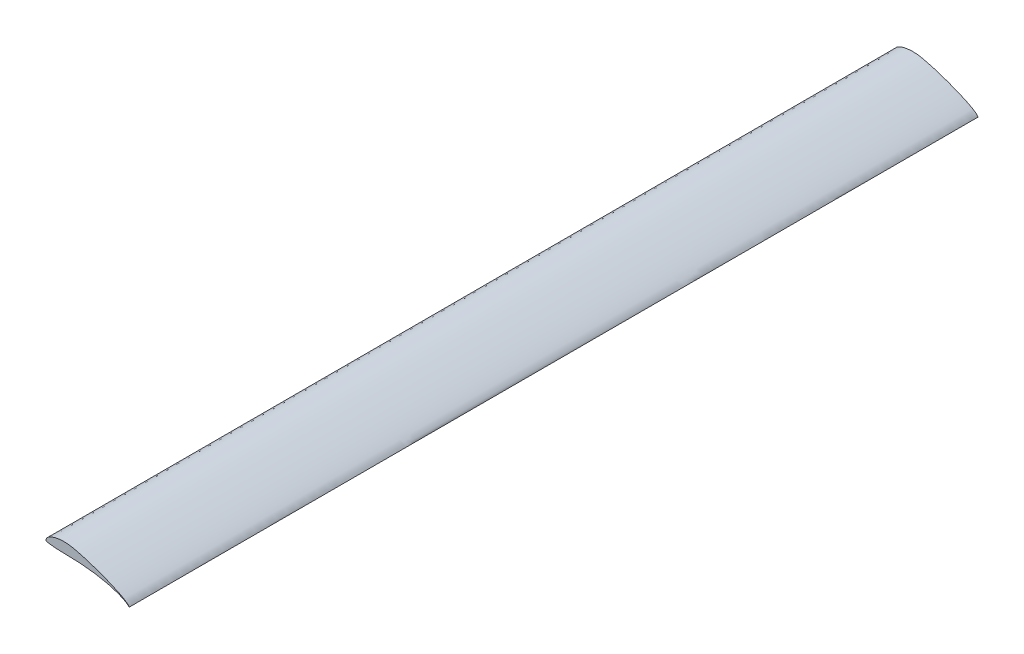
SolidWorks part; units mm, degrees
ref_plane "Front Plane" through (0, 0, 0) normal (0, 0, 1) x (1, 0, 0)
ref_plane "Top Plane" through (0, 0, 0) normal (0, 1, 0) x (1, 0, 0)
ref_plane "Right Plane" through (0, 0, 0) normal (1, 0, 0) x (0, 0, -1)
curve "Curve1"
  spline degree 3 poles (0.9961, 0.0026, 0) (1.0009, -0.0006, 0) (0.9967, 0.0025, 0) (0.9939, 0.0052, 0) (0.9878, 0.0109, 0) (0.9805, 0.017, 0) (0.9705, 0.0231, 0) (0.9581, 0.029, 0) (0.9432, 0.0352, 0) (0.9257, 0.0415, 0) (0.9057, 0.048, 0) (0.8834, 0.0546, 0) (0.8588, 0.0611, 0) (0.8322, 0.0677, 0) (0.8036, 0.0742, 0) (0.7732, 0.0806, 0) (0.7412, 0.0869, 0) (0.7079, 0.0929, 0) (0.6733, 0.0987, 0) (0.6378, 0.1042, 0) (0.6014, 0.1094, 0) (0.5646, 0.1143, 0) (0.5275, 0.1189, 0) (0.4904, 0.1231, 0) (0.4536, 0.1269, 0) (0.4175, 0.1302, 0) (0.3823, 0.1328, 0) (0.3482, 0.1346, 0) (0.3154, 0.1354, 0) (0.284, 0.1353, 0) (0.2541, 0.1338, 0) (0.2258, 0.1307, 0) (0.1988, 0.1263, 0) (0.1732, 0.1206, 0) (0.1489, 0.1139, 0) (0.1262, 0.1063, 0) (0.1051, 0.0981, 0) (0.0858, 0.0892, 0) (0.0682, 0.0798, 0) (0.0525, 0.0701, 0) (0.0388, 0.0602, 0) (0.0271, 0.0502, 0) (0.0176, 0.0401, 0) (0.0103, 0.03, 0) (0.0049, 0.0202, 0) (0.0014, 0.0108, 0) (-0.0002, 0.0022, 0) (0.0001, -0.0051, 0) (0.002, -0.0118, 0) (0.0089, -0.0151, 0) (0.0183, -0.0156, 0) (0.0312, -0.016, 0) (0.0473, -0.0153, 0) (0.0666, -0.0141, 0) (0.0888, -0.012, 0) (0.1137, -0.0092, 0) (0.1411, -0.0057, 0) (0.1711, -0.0007, 0) (0.2038, 0.0055, 0) (0.2393, 0.0123, 0) (0.2775, 0.0195, 0) (0.3182, 0.0267, 0) (0.361, 0.0338, 0) (0.4056, 0.0404, 0) (0.4517, 0.0464, 0) (0.4987, 0.0515, 0) (0.5464, 0.0555, 0) (0.5941, 0.0584, 0) (0.6414, 0.06, 0) (0.6878, 0.0602, 0) (0.7328, 0.059, 0) (0.7758, 0.0564, 0) (0.8164, 0.0525, 0) (0.854, 0.0475, 0) (0.8881, 0.0414, 0) (0.9184, 0.0345, 0) (0.9444, 0.027, 0) (0.9656, 0.0191, 0) (0.9807, 0.0119, 0) (0.9918, 0.0052, 0) (0.9961, 0.0026, 0) (1.0009, -0.0006, 0) (0.9967, 0.0025, 0) knots -0.009748 -0.004147 -0.001 0 0.00098 0.003649 0.007483 0.012095 0.017526 0.024052 0.031783 0.040678 0.05071 0.061833 0.073989 0.087118 0.101145 0.115991 0.13157 0.147788 0.164551 0.181758 0.199312 0.217095 0.23499 0.252857 0.270541 0.287887 0.304773 0.321101 0.336806 0.3518 0.366031 0.379616 0.392653 0.40517 0.417172 0.428604 0.439419 0.449597 0.459102 0.467908 0.475988 0.483309 0.489875 0.495803 0.501149 0.505903 0.510047 0.513579 0.516447 0.51935 0.523823 0.529974 0.537716 0.546968 0.557637 0.56962 0.582804 0.597247 0.613135 0.630444 0.649056 0.668822 0.689595 0.71119 0.733427 0.756094 0.778989 0.80189 0.824567 0.846792 0.868338 0.888978 0.908492 0.926659 0.943286 0.958169 0.971136 0.981956 0.990252 0.995853 0.999 1 1.00098 1.003649 1.007483 periodic
sketch "Sketch1" plane through (0, 0, 0) normal (0, 0, 1) x (1, 0, 0)
  line L0 (17.9899, -2.3134) -> (-1.6004, 1.7142) construction
  line L1 (-1.6004, 1.7142) -> (-1.308, 3.1363) construction
  spline S1 degree 3 poles (17.9245, -2.2469) (18.005, -2.3297) (17.9356, -2.2517) (17.8921, -2.1871) (17.7942, -2.0505) (17.676, -1.9024) (17.5055, -1.7426) (17.2867, -1.5766) (17.0187, -1.3952) (16.7015, -1.2002) (16.3366, -0.9927) (15.9258, -0.7743) (15.4713, -0.5461) (14.9757, -0.3099) (14.4417, -0.0671) (13.8725, 0.1807) (13.2715, 0.4322) (12.6422, 0.685) (11.9887, 0.9382) (11.3144, 1.1895) (10.624, 1.4382) (9.9219, 1.6826) (9.2132, 1.9212) (8.5038, 2.1535) (7.7994, 2.3761) (7.1055, 2.5865) (6.4264, 2.78) (5.7654, 2.953) (5.1254, 3.1007) (4.5104, 3.2257) (3.919, 3.3161) (3.3507, 3.3696) (2.8043, 3.3922) (2.2796, 3.3838) (1.7784, 3.3505) (1.3033, 3.2941) (0.8567, 3.2177) (0.4415, 3.1217) (0.0595, 3.0093) (-0.2868, 2.8823) (-0.5951, 2.7428) (-0.8643, 2.595) (-1.0917, 2.436) (-1.2759, 2.2673) (-1.4216, 2.0963) (-1.5272, 1.9272) (-1.5943, 1.7649) (-1.6175, 1.6207) (-1.6077, 1.482) (-1.4843, 1.3888) (-1.3023, 1.3418) (-1.0526, 1.2811) (-0.7334, 1.2296) (-0.3506, 1.1769) (0.0922, 1.1275) (0.5906, 1.0815) (1.1423, 1.0406) (1.7497, 1.017) (2.415, 1.0073) (3.1384, 0.9968) (3.916, 0.9829) (4.7418, 0.9608) (5.6089, 0.9263) (6.5098, 0.8761) (7.436, 0.8071) (8.3787, 0.7174) (9.3282, 0.6045) (10.2748, 0.4681) (11.2082, 0.308) (12.1181, 0.1247) (12.9942, -0.08) (13.8265, -0.3036) (14.6051, -0.5433) (15.3211, -0.7942) (15.9655, -1.0515) (16.5313, -1.3095) (17.009, -1.5593) (17.3924, -1.7998) (17.6596, -2.0027) (17.8511, -2.1789) (17.9245, -2.2469) (18.005, -2.3297) (17.9356, -2.2517) knots -0.009748 -0.004147 -0.001 0 0.00098 0.003649 0.007483 0.012095 0.017526 0.024052 0.031783 0.040678 0.05071 0.061833 0.073989 0.087118 0.101145 0.115991 0.13157 0.147788 0.164551 0.181758 0.199312 0.217095 0.23499 0.252857 0.270541 0.287887 0.304773 0.321101 0.336806 0.3518 0.366031 0.379616 0.392653 0.40517 0.417172 0.428604 0.439419 0.449597 0.459102 0.467908 0.475988 0.483309 0.489875 0.495803 0.501149 0.505903 0.510047 0.513579 0.516447 0.51935 0.523823 0.529974 0.537716 0.546968 0.557637 0.56962 0.582804 0.597247 0.613135 0.630444 0.649056 0.668822 0.689595 0.71119 0.733427 0.756094 0.778989 0.80189 0.824567 0.846792 0.868338 0.888978 0.908492 0.926659 0.943286 0.958169 0.971136 0.981956 0.990252 0.995853 0.999 1 1.00098 1.003649 1.007483 only from (17.9899, -2.3134) to (17.9899, -2.3134)
  dimension "D1" = 20
extrude "Boss-Extrude1" add sketch "Sketch1" along normal blind 200 contours S1
